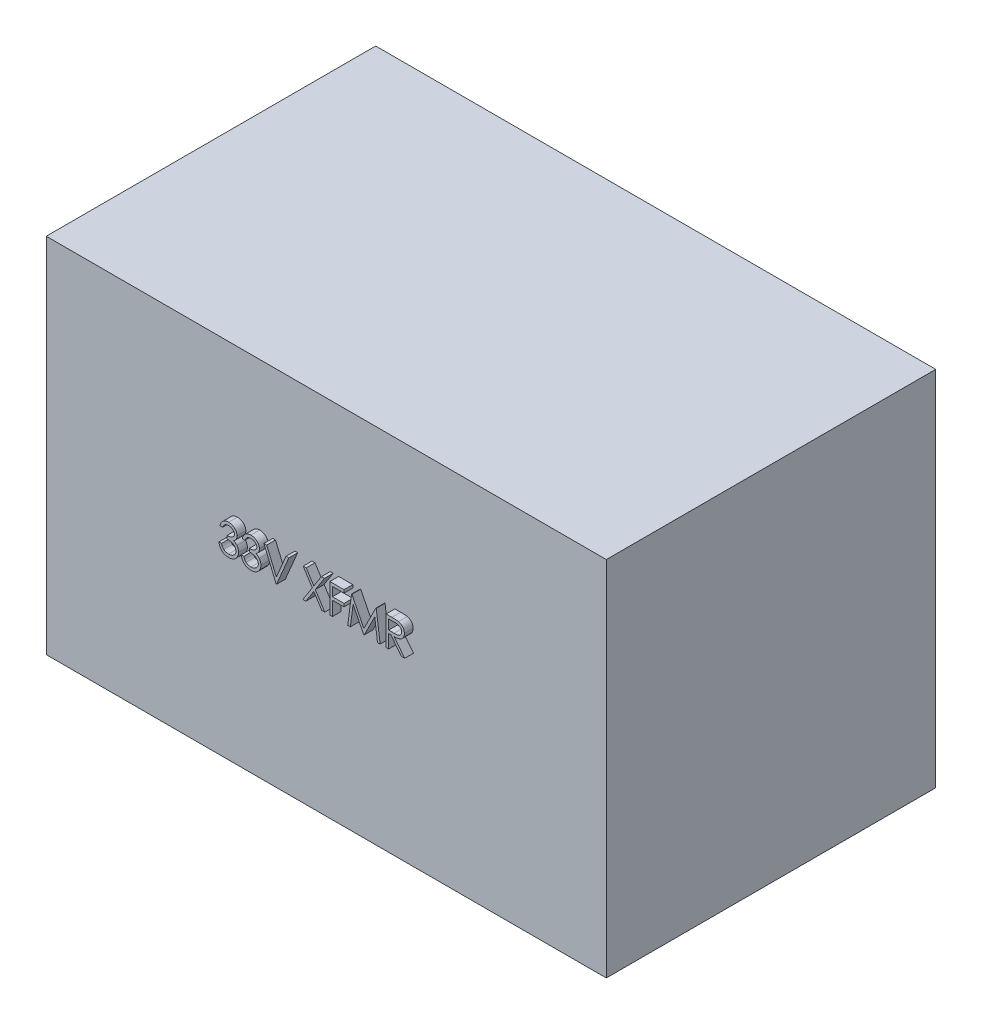
SolidWorks part; units mm, degrees
ref_plane "Front Plane" through (0, 0, 0) normal (0, 0, 1) x (1, 0, 0)
ref_plane "Top Plane" through (0, 0, 0) normal (0, 1, 0) x (1, 0, 0)
ref_plane "Right Plane" through (0, 0, 0) normal (1, 0, 0) x (0, 0, -1)
sketch "Sketch1" plane through (0, 0, 0) normal (0, 1, 0) x (1, 0, 0)
  line L1 (51, -30) -> (-51, -30)
  line L2 (51, -30) -> (51, 30)
  line L3 (51, 30) -> (-51, 30)
  line L4 (-51, -30) -> (-51, 30)
  line L5 (51, -30) -> (-51, 30) construction
  line L6 (51, 30) -> (-51, -30) construction
  point P0 (0, 0)
  dimension "D1" = 102
  dimension "D2" = 60
extrude "Boss-Extrude1" add sketch "Sketch1" along normal blind 66
sketch "Sketch2" plane through (0, 0, 30) normal (0, 0, 1) x (1, 0, 0)
  text T0 "33V XFMR" font "Century Gothic" height in points 20
extrude "Boss-Extrude2" add sketch "Sketch2" along normal blind 1.6
